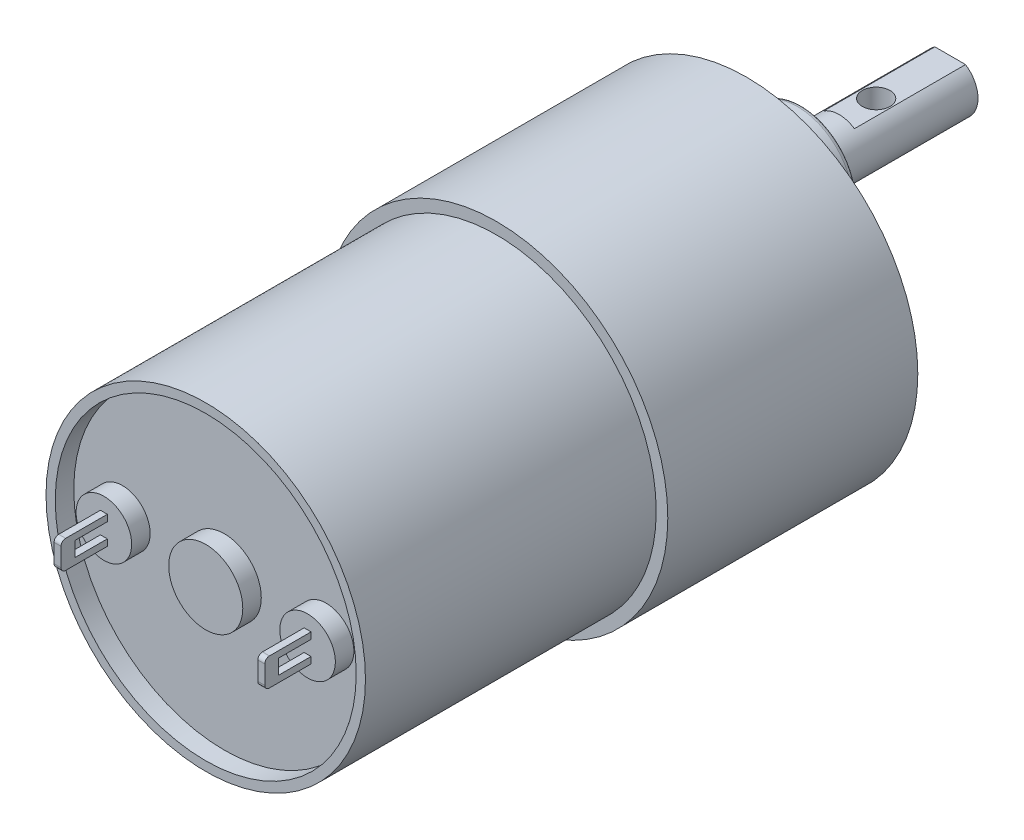
SolidWorks part; units mm, degrees
material "6061 Alloy"
ref_plane "Alzado" through (0, 0, 0) normal (0, 0, 1) x (1, 0, 0)
ref_plane "Planta" through (0, 0, 0) normal (0, 1, 0) x (1, 0, 0)
ref_plane "Vista lateral" through (0, 0, 0) normal (1, 0, 0) x (0, 0, -1)
sketch "Croquis1" plane through (0, 0, 0) normal (0, 0, 1) x (1, 0, 0)
  circle A0 centre (0, 0) radius 17.25
  dimension "D1" = 34.5
extrude "Saliente-Extruir1" add sketch "Croquis1" along normal blind 31.4
sketch "Croquis2" plane through (0, 0, 0) normal (0, 0, -1) x (-1, 0, 0)
  circle A0 centre (0, 0) radius 18.5
  dimension "D1" = 37
extrude "Saliente-Extruir2" add sketch "Croquis2" along normal blind 27
sketch "Croquis3" plane through (0, 0, -27) normal (0, 0, -1) x (-1, 0, 0)
  circle A0 centre (0, 7) radius 6
  circle A2 centre (0, 0) radius 18.5 construction
  point P5 (0, 1)
  point P6 (0, 18.5)
  dimension "D1" = 12
  dimension "D2" = 17.5
extrude "Saliente-Extruir3" add sketch "Croquis3" along normal blind 6
sketch "Croquis4" plane through (0, 0, -33) normal (0, 0, -1) x (-1, 0, 0)
  circle A0 centre (0, 7) radius 3
  dimension "D1" = 6
extrude "Saliente-Extruir4" add sketch "Croquis4" along normal blind 16
sketch "Croquis5" plane through (0, 0, -49) normal (0, 0, -1) x (-1, 0, 0)
  line L0 (-1.6583, 9.5) -> (1.6583, 9.5)
  line L1 (0, 4) -> (0, 9.5) construction
  circle A0 centre (0, 7) radius 3 construction
  circle A1 centre (0, 7) radius 3 construction
  arc A2 (1.6583, 9.5) -> (-1.6583, 9.5) centre (0, 7) ccw
  dimension "D1" = 5.5
extrude "Cortar-Extruir1" cut sketch "Croquis5" against normal blind 12
sketch "Croquis8" plane through (0, 0, 31.4) normal (0, 0, 1) x (1, 0, 0)
  circle A1 centre (0, 0) radius 4
  circle A2 centre (0, 0) radius 16.25
  circle A3 centre (0, 0) radius 16.25
  dimension "D2" = 8
  dimension "D1" = 1
extrude "Cortar-Extruir2" cut sketch "Croquis8" against normal blind 2
sketch "Croquis9" plane through (0, 0, 29.4) normal (0, 0, 1) x (1, 0, 0)
  circle A0 centre (-11, 0) radius 3
  circle A1 centre (11, 0) radius 3
  dimension "D1" = 6
  dimension "D2" = 11
  dimension "D3" = 11
extrude "Saliente-Extruir5" add sketch "Croquis9" along normal blind 2 separate body
sketch "Croquis10" plane through (0, 0, 31.4) normal (0, 0, 1) x (1, 0, 0)
  line L0 (0, 0) -> (0, -4) construction
  line L1 (-10.625, 1.5) -> (-11.375, 1.5)
  line L2 (-10.625, 1.5) -> (-10.625, -1.5)
  line L3 (-10.625, -1.5) -> (-11.375, -1.5)
  line L4 (-11.375, 1.5) -> (-11.375, -1.5)
  line L5 (-10.625, 1.5) -> (-11.375, -1.5) construction
  line L6 (-10.625, -1.5) -> (-11.375, 1.5) construction
  line L7 (10.625, -1.5) -> (11.375, -1.5)
  line L8 (11.375, 1.5) -> (11.375, -1.5)
  line L9 (10.625, 1.5) -> (11.375, 1.5)
  line L10 (10.625, 1.5) -> (10.625, -1.5)
  circle A0 centre (0, 0) radius 4 construction
  point P0 (-11, 0)
  dimension "D1" = 0.75
  dimension "D2" = 3
extrude "Saliente-Extruir6" add sketch "Croquis10" along normal blind 5 separate body
sketch "Croquis11" plane through (-11.375, 0, 0) normal (-1, 0, 0) x (0, 0, 1)
  line L0 (31.4, 1.5) -> (31.4, -1.5) construction
  line L1 (31.4, 0.8) -> (34.9, 0.8)
  line L2 (31.4, 0.8) -> (31.4, -0.8)
  line L3 (31.4, -0.8) -> (34.9, -0.8)
  line L4 (34.9, 0.8) -> (34.9, -0.8)
  line L5 (36.4, 1.5) -> (36.4, -1.5) construction
  line L6 (36.4, 1.5) -> (31.4, 1.5) construction
  point P6 (34.9, 0)
  point P9 (36.4, 0)
  dimension "D1" = 0.7
  dimension "D2" = 1.5
extrude "Cortar-Extruir3" cut sketch "Croquis11" against normal up to surface (22.75 mm away)
fillet "Redondeo1" radius 0.5 2 edges at (-11, 1.5, 36.4) (-11, -1.5, 36.4)
fillet "Redondeo2" radius 0.5 2 edges at (11, -1.5, 36.4) (11, 1.5, 36.4)
fillet "Redondeo3" radius 0.5 1 edges at (-6, 7, -33)
sketch "Croquis12" plane through (0, 0, -27) normal (0, 0, -1) x (-1, 0, 0)
  line L0 (0, 0) -> (-15.5, 0) construction
  circle A0 centre (0, 0) radius 15.5 construction
  circle A1 centre (-15.5, 0) radius 1.5
  circle A2 centre (-7.75, 13.4234) radius 1.5
  circle A3 centre (7.75, 13.4234) radius 1.5
  circle A4 centre (15.5, 0) radius 1.5
  circle A5 centre (7.75, -13.4234) radius 1.5
  circle A6 centre (-7.75, -13.4234) radius 1.5
  dimension "D1" = 31
  dimension "D2" = 3
  dimension "D4" = 15.5
  dimension "D3" = 6
extrude "Cortar-Extruir4" cut sketch "Croquis12" against normal blind 3
sketch "Sketch1" plane through (0, 9.5, 0) normal (0, 1, 0) x (1, 0, 0)
  line L0 (1.6583, 49) -> (-1.6583, 49) construction
  circle A0 centre (0, 41) radius 1.5
  dimension "D2" = 3
  dimension "D1" = 8
extrude "Cut-Extrude1" cut sketch "Sketch1" against normal up to next
